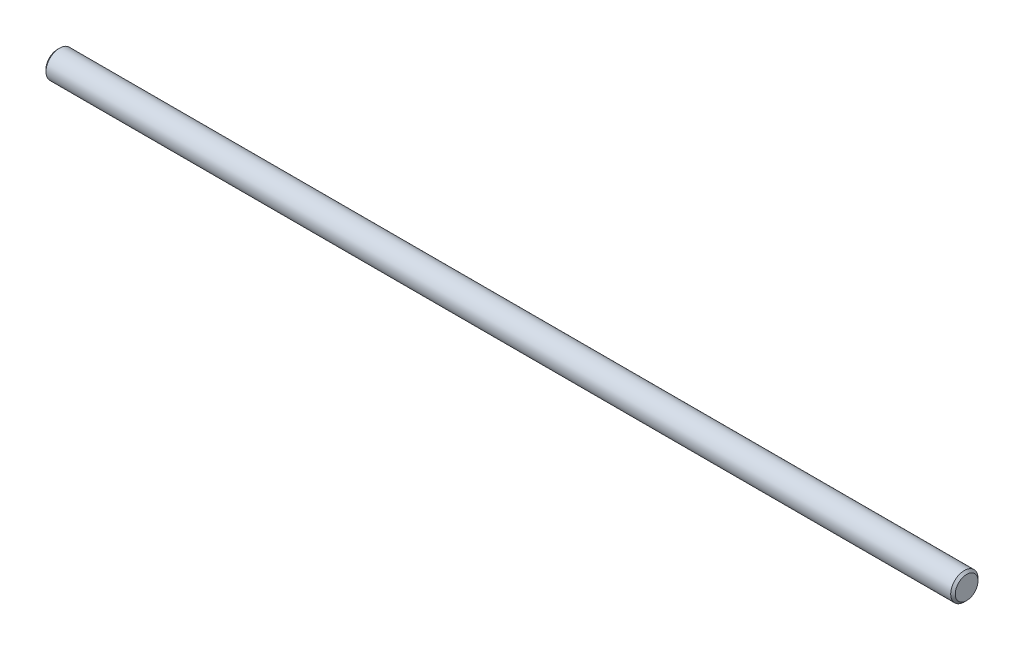
SolidWorks part; units mm, degrees
material "Chrome Stainless Steel"
ref_plane "Front Plane" through (0, 0, 0) normal (0, 0, 1) x (1, 0, 0)
ref_plane "Top Plane" through (0, 0, 0) normal (0, 1, 0) x (1, 0, 0)
ref_plane "Right Plane" through (0, 0, 0) normal (1, 0, 0) x (0, 0, -1)
sketch "Sketch1" plane through (0, 0, 0) normal (1, 0, 0) x (0, 0, -1)
  circle A0 centre (0, 0) radius 6
  dimension "D1" = 12
extrude "Boss-Extrude1" add sketch "Sketch1" along normal blind 400
chamfer "Chamfer1" distance 1 angle 45 2 edges at (400, 0, -6) (0, 0, -6)
